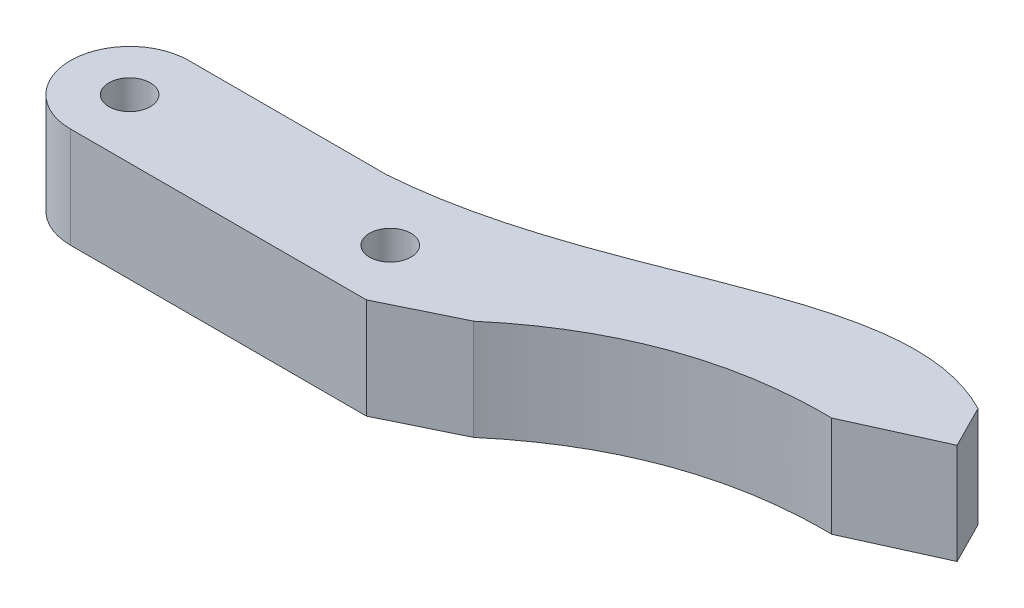
SolidWorks part; units mm, degrees
ref_plane "Front Plane" through (0, 0, 0) normal (0, 0, 1) x (1, 0, 0)
ref_plane "Top Plane" through (0, 0, 0) normal (0, 1, 0) x (1, 0, 0)
ref_plane "Right Plane" through (0, 0, 0) normal (1, 0, 0) x (0, 0, -1)
sketch "Sketch1" plane through (0, 0, 0) normal (0, 1, 0) x (1, 0, 0)
  line L1 (-5, 5) -> (27, 5)
  line L2 (-5, 5) -> (-5, -5)
  line L3 (-5, -5) -> (27, -5)
  line L4 (27, 5) -> (27, -5)
  line L5 (-5, 5) -> (27, -5) construction
  line L6 (-5, -5) -> (27, 5) construction
  circle A0 centre (0, 0) radius 5
  circle A1 centre (0, 0) radius 1.75
  circle A2 centre (22, 0) radius 5
  circle A3 centre (22, 0) radius 1.75
  point P7 (11, 0)
  point P12 (0, 0)
  dimension "D1" = 22
  dimension "D2" = 10
  dimension "D3" = 3.5
extrude "Boss-Extrude1" add sketch "Sketch1" along normal blind 8.5 contours A0 A1 | A2 L1 A0 L3 | A2 A3
sketch "Sketch2" plane through (0, 8.5, 0) normal (0, 1, 0) x (1, 0, 0)
  line L0 (22, -5) -> (24.99, -5)
  line L1 (24.99, -5) -> (31.08, -2.0297)
  line L2 (0, 5) -> (22, 5) construction
  line L3 (58.75, 12.87) -> (60.557, 9.3014)
  line L4 (60.557, 9.3014) -> (53.27, 6)
  line L5 (0, -5) -> (22, -5) construction
  line L6 (11, 5) -> (22, 5)
  circle A0 centre (22, 0) radius 1.75 construction
  arc A1 (22, -5) -> (22, 5) centre (22, 0) ccw construction
  arc A2 (22, -5) -> (22, 5) centre (22, 0) ccw
  spline S0 degree 3 poles (11, 5) (31.6165, 3.4376) (45.7056, 19.6384) (58.75, 12.87) knots 0 0 0 0 1 1 1 1
  spline S1 degree 2 poles (31.08, -2.0297) (40.7387, 6.1883) (53.27, 6) knots 0 0 0 1 1 1
  point P16 (31.3093, 11.2477)
  point P17 (33.3543, 11.3182)
  point P18 (33.4953, 10.3309)
  point P19 (40.5472, 4.4074)
  arc M4 (22, -5) -> (22, 5) centre (22, 0) ccw
  line M5 (22, 5) -> (0, 5)
  dimension "D1" = 4
  dimension "D2" = 8
  dimension "D3" = 17.87
  dimension "D4" = 11
  dimension "D5" = 26
  dimension "D6" = 36.75
  dimension "D7" = 47.75
  dimension "D8" = 2.99
  dimension "D9" = 9.08
  dimension "D10" = 13.52
  dimension "D11" = 20.52
  dimension "D12" = 31.27
  dimension "D13" = 9.45
  dimension "D14" = 15.03
extrude "Boss-Extrude2" add sketch "Sketch2" against normal blind 8.5 contours L1 S1 L4 L3 S0 L0 M5 M4
